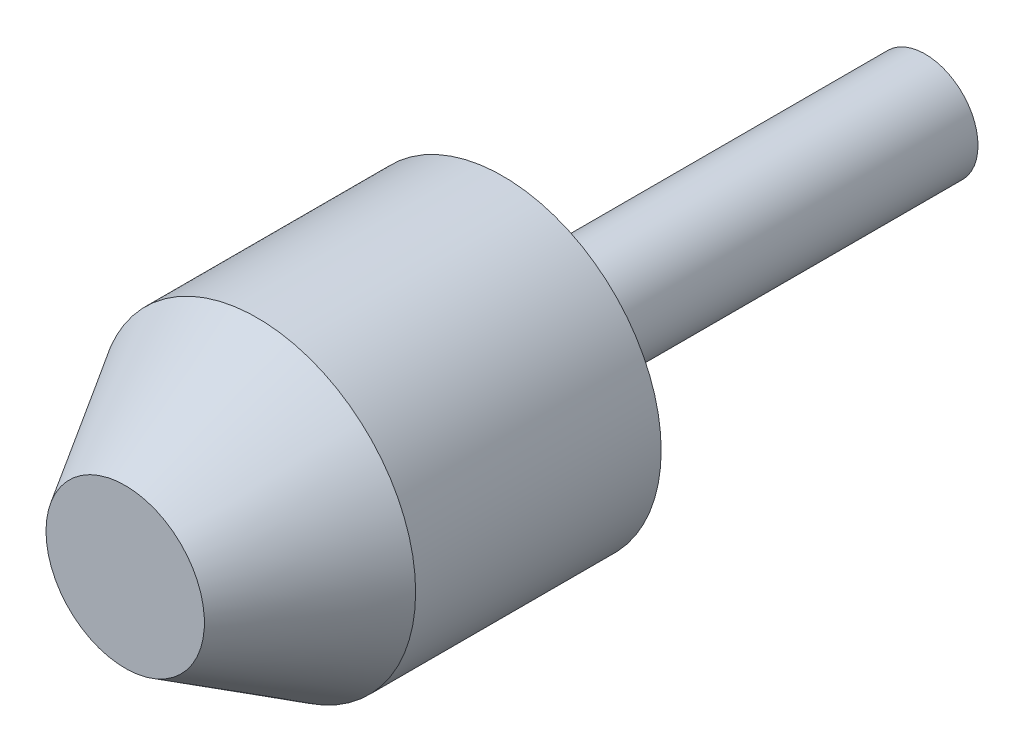
SolidWorks part; units mm, degrees
material "灰铸铁"
ref_plane "前视基准面" through (0, 0, 0) normal (0, 0, 1) x (1, 0, 0)
ref_plane "上视基准面" through (0, 0, 0) normal (0, 1, 0) x (1, 0, 0)
ref_plane "右视基准面" through (0, 0, 0) normal (1, 0, 0) x (0, 0, -1)
sketch "草图1" plane through (0, 0, 0) normal (0, 0, 1) x (1, 0, 0)
  circle A0 centre (0, 0) radius 2
  dimension "D1" = 4
extrude "凸台-拉伸1" add sketch "草图1" along normal blind 16
sketch "草图2" plane through (0, 0, 16) normal (0, 0, 1) x (1, 0, 0)
  circle A0 centre (0, 0) radius 6
  dimension "D1" = 12
extrude "凸台-拉伸2" add sketch "草图2" along normal blind 14.3
sketch "草图3" plane through (0, 0, 0) normal (0, 1, 0) x (1, 0, 0)
  line L0 (-3, -30.3) -> (-6, -25.3)
  line L1 (-6, -16) -> (-6, -30.3) construction
  line L2 (-6, -25.3) -> (-3, -25.3) construction
  line L3 (-3, -25.3) -> (-3, -30.3) construction
  line L4 (-6, -30.3) -> (6, -30.3) construction
  line L5 (0, 0) -> (0, -30.3) construction
  line L6 (-6, -25.3) -> (-6, -30.3)
  line L7 (-6, -30.3) -> (-3, -30.3)
  dimension "D1" = 3
  dimension "D2" = 5
revolve "切除-旋转2" cut sketch "草图3" angle 360 about L5
